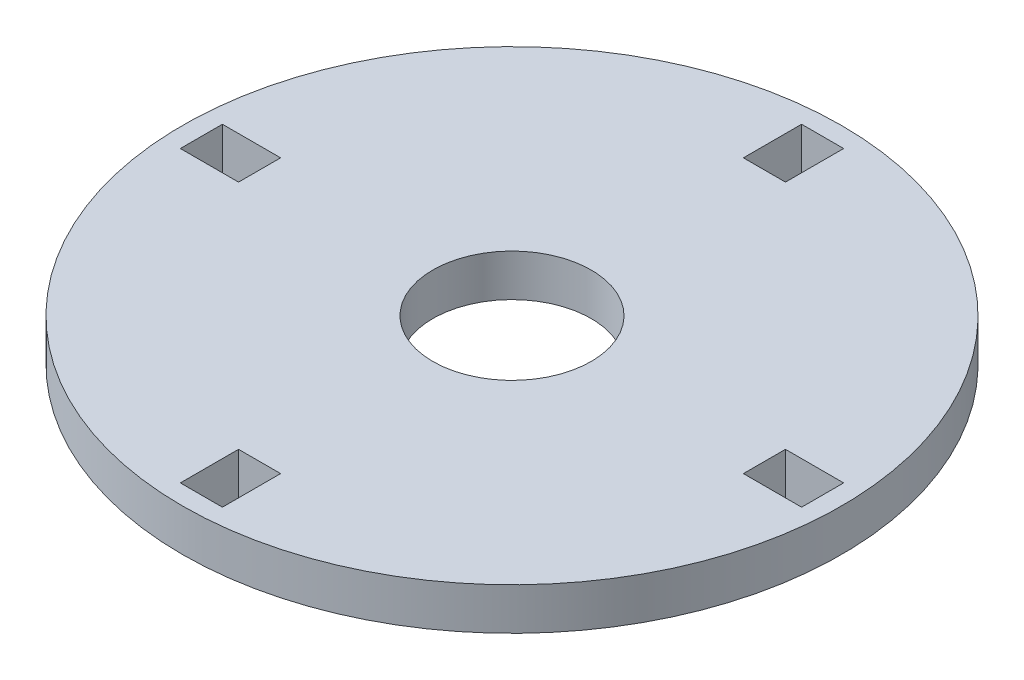
SolidWorks part; units mm, degrees
ref_plane "Přední rovina" through (0, 0, 0) normal (0, 0, 1) x (1, 0, 0)
ref_plane "Horní rovina" through (0, 0, 0) normal (0, 1, 0) x (1, 0, 0)
ref_plane "Pravá rovina" through (0, 0, 0) normal (1, 0, 0) x (0, 0, -1)
sketch "Skica1" plane through (0, 0, 0) normal (0, 1, 0) x (1, 0, 0)
  circle A0 centre (0, 0) radius 23.5
  dimension "D1" = 47
extrude "Přidat vysunutím1" add sketch "Skica1" along normal blind 3
sketch "Skica2" plane through (0, 3, 0) normal (0, 1, 0) x (1, 0, 0)
  circle A0 centre (0, 0) radius 5.65
  dimension "D1" = 11.3
extrude "Odebrat vysunutím1" cut sketch "Skica2" against normal blind 3
sketch "Skica3" plane through (0, 0, 0) normal (0, -1, 0) x (1, 0, 0)
  line L0 (0, 25.338) -> (0, -28.6539) construction
  line L1 (24.6811, 0) -> (-25.3693, 0) construction
  line L2 (22.15, 1.5) -> (18, 1.5)
  line L3 (-1.5, 22.15) -> (1.5, 22.15)
  line L4 (-1.5, 22.15) -> (-1.5, 18)
  line L5 (-1.5, 18) -> (1.5, 18)
  line L6 (1.5, 22.15) -> (1.5, 18)
  line L7 (-1.5, 22.15) -> (1.5, 18) construction
  line L8 (-1.5, 18) -> (1.5, 22.15) construction
  line L9 (22.15, 1.5) -> (22.15, -1.5)
  line L10 (22.15, -1.5) -> (18, -1.5)
  line L11 (18, 1.5) -> (18, -1.5)
  line L12 (1.5, -22.15) -> (1.5, -18)
  line L13 (1.5, -22.15) -> (-1.5, -22.15)
  line L14 (-1.5, -22.15) -> (-1.5, -18)
  line L15 (1.5, -18) -> (-1.5, -18)
  line L16 (-22.15, -1.5) -> (-18, -1.5)
  line L17 (-22.15, -1.5) -> (-22.15, 1.5)
  line L18 (-22.15, 1.5) -> (-18, 1.5)
  line L19 (-18, -1.5) -> (-18, 1.5)
  point P5 (0, 20.075)
  point P25 (0, 0)
  dimension "D1" = 18
  dimension "D2" = 4.15
  dimension "D3" = 3
  dimension "D4" = 4
extrude "Odebrat vysunutím2" cut sketch "Skica3" against normal blind 3
